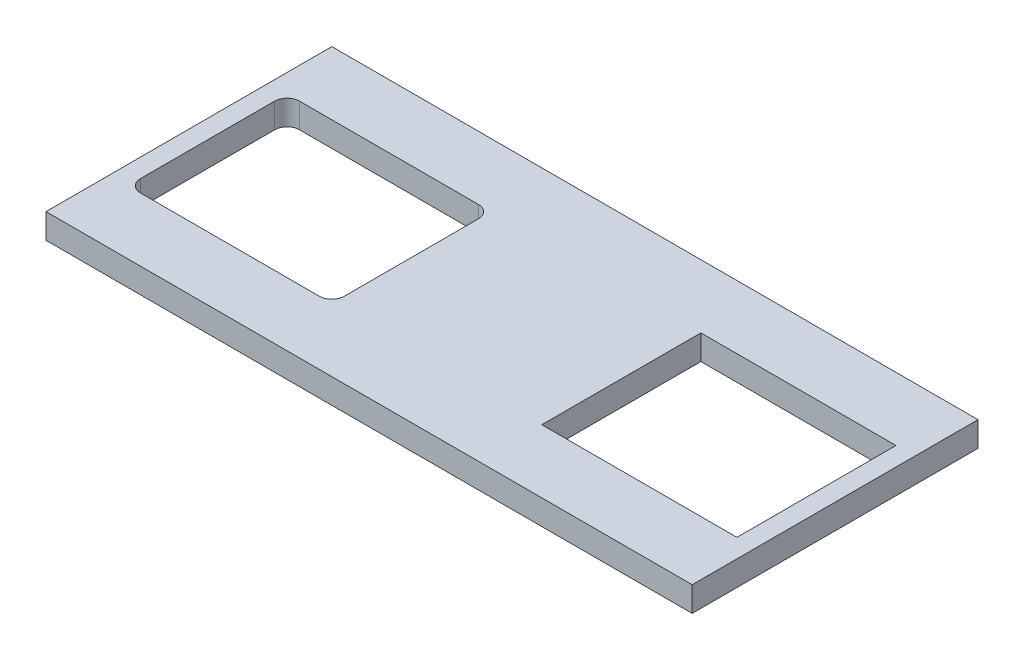
SolidWorks part; units mm, degrees
ref_plane "Front Plane" through (0, 0, 0) normal (0, 0, 1) x (1, 0, 0)
ref_plane "Top Plane" through (0, 0, 0) normal (0, 1, 0) x (1, 0, 0)
ref_plane "Right Plane" through (0, 0, 0) normal (1, 0, 0) x (0, 0, -1)
sketch "Sketch1" plane through (0, 0, 0) normal (0, 1, 0) x (1, 0, 0)
  line L1 (0, 0) -> (-260, 0)
  line L2 (0, 0) -> (0, 115)
  line L3 (0, 115) -> (-260, 115)
  line L4 (-260, 0) -> (-260, 115)
  line L5 (-247.5, 89.5) -> (-175.5, 89.5)
  line L6 (-252.5, 84.5) -> (-252.5, 30.5)
  line L7 (-247.5, 25.5) -> (-175.5, 25.5)
  line L8 (-170.5, 84.5) -> (-170.5, 30.5)
  line L9 (-85.9931, 89.5) -> (-7.5, 89.5)
  line L10 (-85.9931, 89.5) -> (-85.9931, 25.5)
  line L11 (-85.9931, 25.5) -> (-7.5, 25.5)
  line L12 (-7.5, 89.5) -> (-7.5, 25.5)
  arc A0 (-252.5, 30.5) -> (-247.5, 25.5) centre (-247.5, 30.5) ccw
  arc A1 (-170.5, 30.5) -> (-175.5, 25.5) centre (-175.5, 30.5) cw
  arc A2 (-170.5, 84.5) -> (-175.5, 89.5) centre (-175.5, 84.5) ccw
  arc A3 (-247.5, 89.5) -> (-252.5, 84.5) centre (-247.5, 84.5) ccw
  circle A4 centre (-243.3, 80.3) radius 3.25
  point P9 (-252.5, 57.5)
  point P10 (-260, 57.5)
  point P17 (-252.5, 25.5)
  point P20 (-170.5, 25.5)
  point P23 (-170.5, 89.5)
  dimension "D7" = 5
  dimension "D8" = 9.2
  dimension "D10" = 6.5
  dimension "D1" = 260
  dimension "D2" = 115
  dimension "D3" = 82
  dimension "D4" = 64
  dimension "D5" = 245
  dimension "D6" = 7.5
  dimension "D9" = 9.2
extrude "Boss-Extrude1" add sketch "Sketch1" along normal blind 10 contours L4 L1 L2 L3 A3 L5 A2 L8 A1 L7 A0 L6 L9 L12 L11 L10
